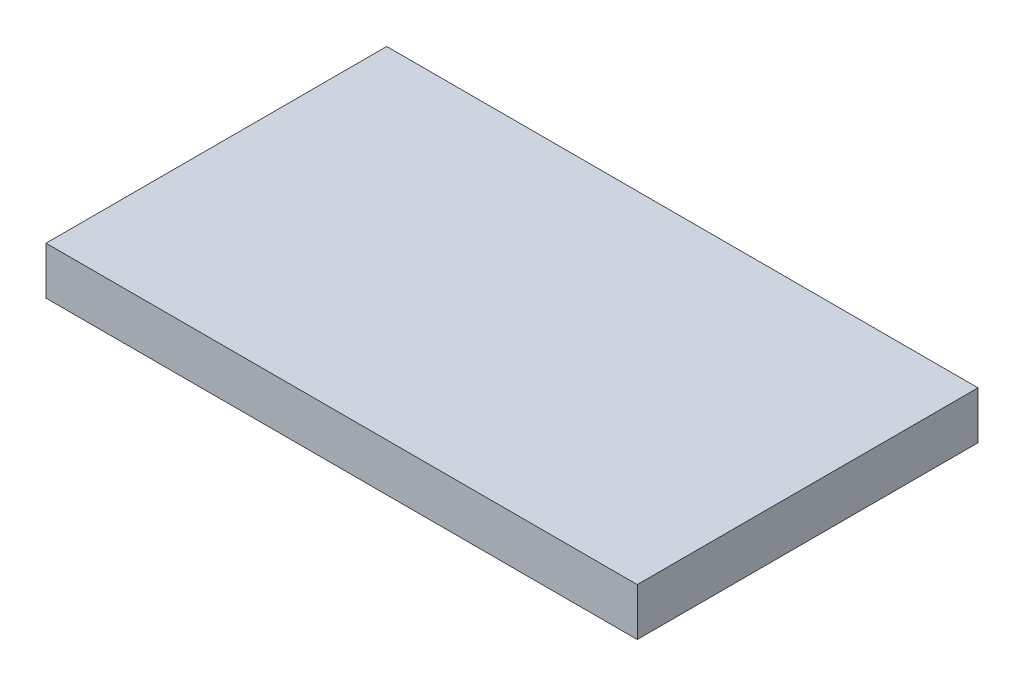
SolidWorks part; units mm, degrees
ref_plane "Front Plane" through (0, 0, 0) normal (0, 0, 1) x (1, 0, 0)
ref_plane "Top Plane" through (0, 0, 0) normal (0, 1, 0) x (1, 0, 0)
ref_plane "Right Plane" through (0, 0, 0) normal (1, 0, 0) x (0, 0, -1)
sketch "Sketch1" plane through (0, 0, 0) normal (0, 1, 0) x (1, 0, 0)
  line L1 (0, 0) -> (-118, 0)
  line L2 (0, 0) -> (0, 68)
  line L3 (0, 68) -> (-118, 68)
  line L4 (-118, 0) -> (-118, 68)
  dimension "D1" = 118
  dimension "D2" = 68
extrude "Boss-Extrude1" add sketch "Sketch1" along normal blind 9.5
